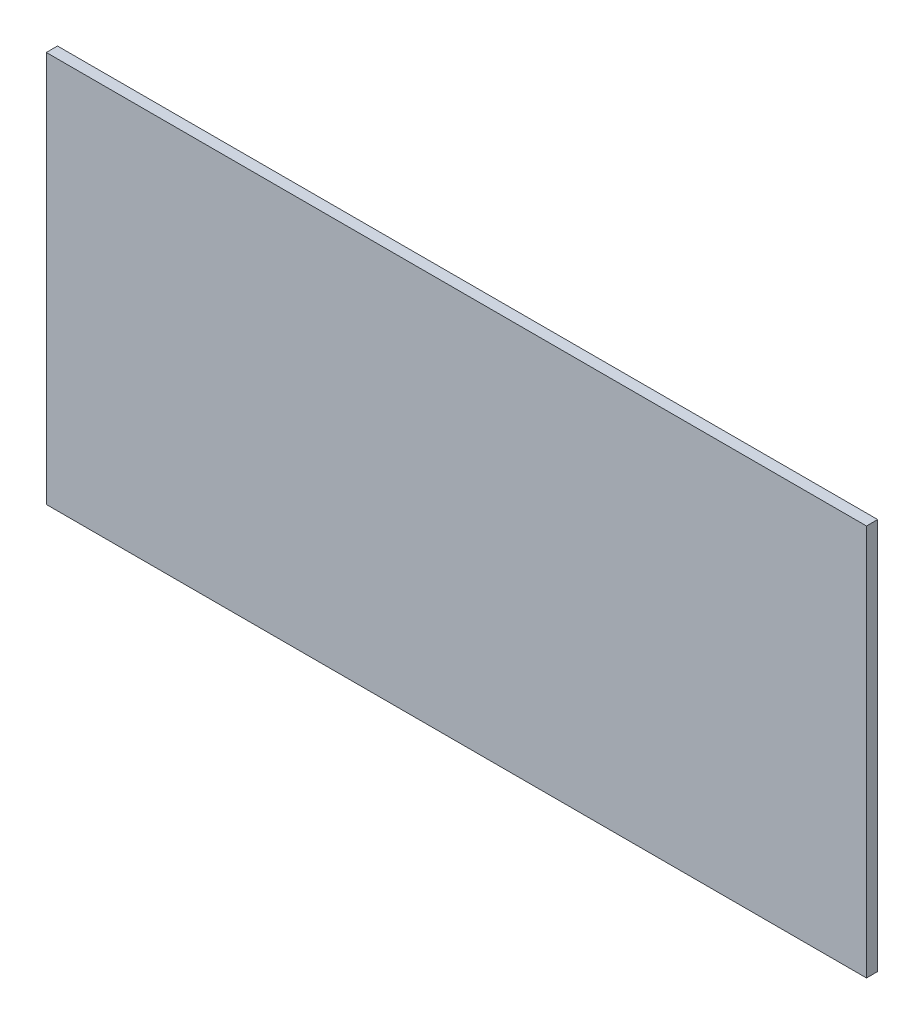
SolidWorks part; units mm, degrees
ref_plane "Front Plane" through (0, 0, 0) normal (0, 0, 1) x (1, 0, 0)
ref_plane "Top Plane" through (0, 0, 0) normal (0, 1, 0) x (1, 0, 0)
ref_plane "Right Plane" through (0, 0, 0) normal (1, 0, 0) x (0, 0, -1)
sketch "Sketch1" plane through (0, 0, 0) normal (0, 0, 1) x (1, 0, 0)
  line L1 (-139.7, -66.675) -> (139.7, -66.675)
  line L2 (-139.7, -66.675) -> (-139.7, 66.675)
  line L3 (-139.7, 66.675) -> (139.7, 66.675)
  line L4 (139.7, -66.675) -> (139.7, 66.675)
  line L5 (-139.7, -66.675) -> (139.7, 66.675) construction
  line L6 (-139.7, 66.675) -> (139.7, -66.675) construction
  point P0 (0, 0)
  dimension "D1" = 279.4
  dimension "D2" = 133.35
extrude "Boss-Extrude1" add sketch "Sketch1" along normal blind 3.81
